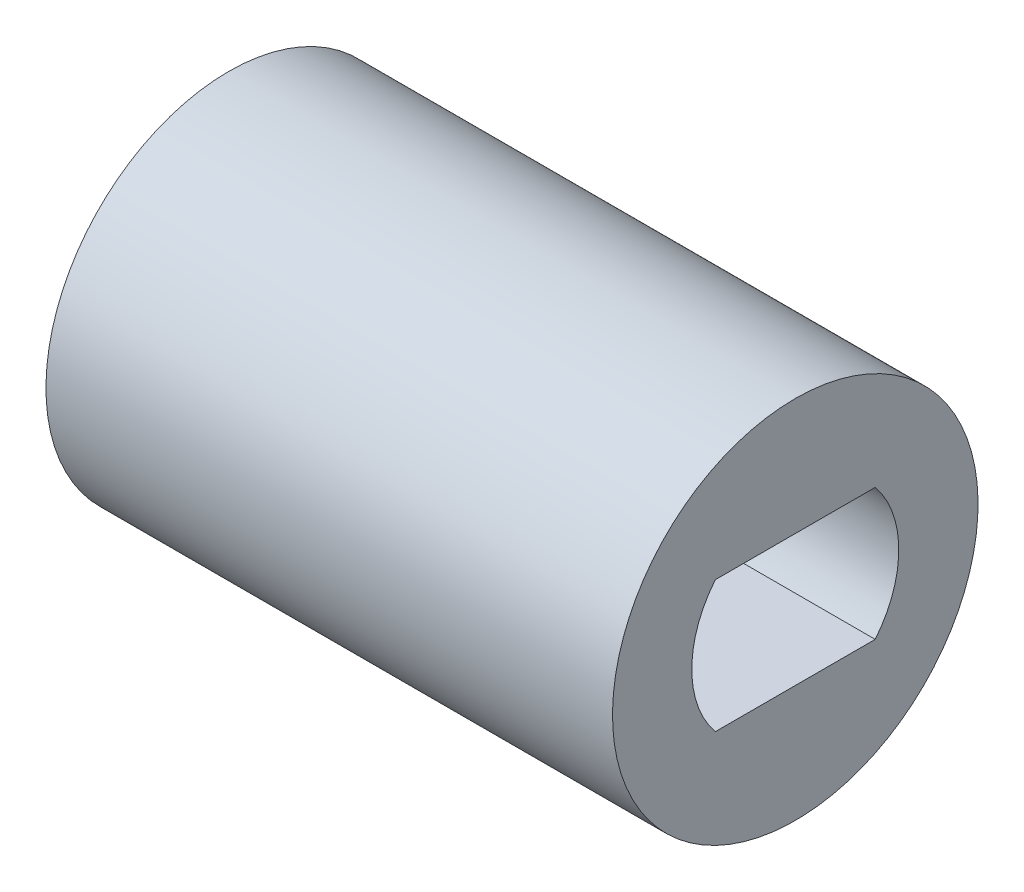
SolidWorks part; units mm, degrees
ref_plane "Front Plane" through (0, 0, 0) normal (0, 0, 1) x (1, 0, 0)
ref_plane "Top Plane" through (0, 0, 0) normal (0, 1, 0) x (1, 0, 0)
ref_plane "Right Plane" through (0, 0, 0) normal (1, 0, 0) x (0, 0, -1)
sketch "Sketch2" plane through (0, 0, 0) normal (0, 0, 1) x (1, 0, 0)
  line L10 (60.96, 6.35) -> (60.96, 0)
  line L11 (60.96, 0) -> (54.102, 0)
  line L17 (41.275, 6.35) -> (60.96, 6.35)
  line L18 (41.275, 6.35) -> (41.275, 3.175)
  line L19 (41.275, 3.175) -> (50.927, 3.175)
  line L20 (50.927, 3.175) -> (54.102, 0)
  point P0 (54.102, 3.175)
  dimension "D1" = 6.35
  dimension "D2" = 6.858
  dimension "D3" = 3.175
  dimension "D4" = 9.652
  dimension "D5" = 225
revolve "Revolve1" add sketch "Sketch2" angle 360 about L11
sketch "Sketch4" plane through (60.96, 0, 0) normal (1, 0, 0) x (0, 0, -1)
  circle A0 centre (0, 0) radius 3.429
  dimension "D1" = 6.858
extrude "Cut-Extrude1" [suppressed] cut sketch "Sketch4" against normal blind 5.715
sketch "Sketch8" plane through (60.96, 0, 0) normal (1, 0, 0) x (0, 0, -1)
  line L0 (-2.7765, 2.286) -> (2.7765, 2.286)
  line L1 (-2.7765, -2.286) -> (2.7765, -2.286)
  circle A0 centre (0, 0) radius 3.5965
  point P8 (0, 0)
  dimension "D1" = 2.286
  dimension "D3" = 7.193
  dimension "D2" = 2.286
extrude "Cut-Extrude2" cut sketch "Sketch8" against normal blind 6.604 contours L0 A0 L1
ref_plane "Plane1" [suppressed] through (0, 7.62, 0) normal (0, 1, 0) x (1, 0, 0)
sketch "Sketch5" [suppressed] plane through (0, 7.62, 0) normal (0, 1, 0) x (1, 0, 0)
  line L0 (60.96, -6.35) -> (60.96, 6.35) construction
  point P0 (57.15, 0)
  dimension "D1" = 3.81
hole_wizard "#32 (0.116) Diameter Hole1" [suppressed] positions "Sketch6" profile "Sketch7" hole size "#32" standard "ANSI Inch"
sketch "Sketch6" [suppressed] plane through (0, 7.62, 0) normal (0, 1, 0) x (1, 0, 0)
  point P0 (57.15, 0)
sketch "Sketch7" plane through (57.15, 7.62, 0) normal (1, 0, 0) x (0, 0, 1)
  line L0 (0, 0) -> (0, 39.37)
  line L1 (0, 39.37) -> (1.4732, 39.37)
  line L2 (1.4732, 39.37) -> (1.4732, 0)
  line L5 (1.4732, 0) -> (0, 0)
  line L11 (0, -6.35) -> (0, 107.95) construction
  dimension "Thru Hole Dia." = 2.9464
  dimension "Thru Hole Depth" = 39.37
equation "\"width_of_film\"= 1.4'a lil more than 35mm"
